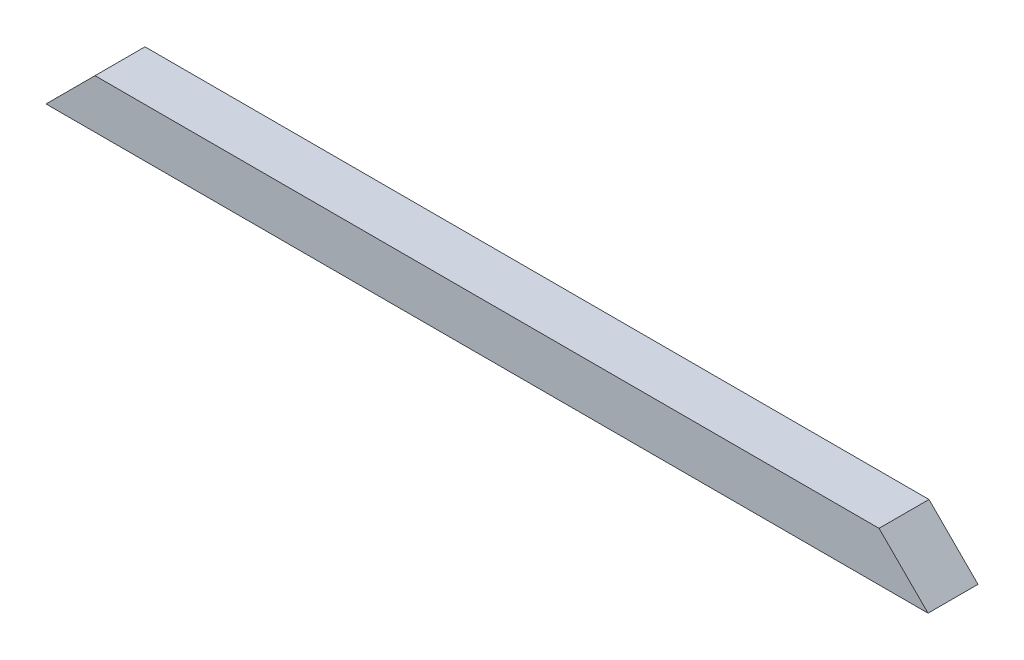
SolidWorks part; units mm, degrees
ref_plane "Alzado" through (0, 0, 0) normal (0, 0, 1) x (1, 0, 0)
ref_plane "Planta" through (0, 0, 0) normal (0, 1, 0) x (1, 0, 0)
ref_plane "Vista lateral" through (0, 0, 0) normal (1, 0, 0) x (0, 0, -1)
sketch "Croquis1" plane through (0, 0, 0) normal (0, 0, 1) x (1, 0, 0)
  line L1 (457.2, -25.4) -> (-457.2, -25.4)
  line L2 (457.2, -25.4) -> (457.2, 25.4)
  line L3 (457.2, 25.4) -> (-457.2, 25.4)
  line L4 (-457.2, -25.4) -> (-457.2, 25.4)
  line L5 (457.2, -25.4) -> (-457.2, 25.4) construction
  line L6 (457.2, 25.4) -> (-457.2, -25.4) construction
  point P0 (0, 0)
  dimension "D1" = 914.4
  dimension "D2" = 50.8
extrude "Saliente-Extruir1" add sketch "Croquis1" along normal blind 50.8 and the other way blind 1
sketch "Croquis3" plane through (0, 0, 50.8) normal (0, 0, 1) x (1, 0, 0)
  line L0 (-457.2, -25.4) -> (457.2, -25.4) construction
  line L1 (-457.2, 25.4) -> (-437.2, 25.4)
  line L2 (-457.2, 25.4) -> (-457.2, -25.4)
  line L3 (-457.2, -25.4) -> (-437.2, -25.4)
  line L4 (-437.2, 25.4) -> (-437.2, -25.4)
  line L5 (-437.2, 25.4) -> (-457.2, -25.4)
  line L6 (0, 0) -> (0, 51.0036) construction
  line M2 (-457.2, 25.4) -> (-457.2, -25.4)
  line M5 (457.2, 25.4) -> (-457.2, 25.4)
  dimension "D1" = 20
extrude "Cortar-Extruir2" cut sketch "Croquis3" against normal through all contours L5 M5 M2
sketch "Croquis4" plane through (0, 0, -1) normal (0, 0, -1) x (-1, 0, 0)
  line L0 (457.2, -25.4) -> (-457.2, -25.4) construction
  line L1 (-457.2, 25.4) -> (-437.2, 25.4)
  line L2 (-457.2, 25.4) -> (-457.2, -25.4)
  line L3 (-457.2, -25.4) -> (-437.2, -25.4)
  line L4 (-437.2, 25.4) -> (-437.2, -25.4)
  line L5 (-457.2, -25.4) -> (-437.2, 25.4)
  line M3 (437.2, 25.4) -> (-457.2, 25.4)
  line M4 (-457.2, 25.4) -> (-457.2, -25.4)
  dimension "D1" = 20
extrude "Cortar-Extruir3" cut sketch "Croquis4" against normal through all contours L5 M4 M3
sketch "Croquis6" plane through (0, 0, 50.8) normal (0, 0, 1) x (1, 0, 0)
  line L0 (437.2, 25.4) -> (-437.2, 25.4) construction
  line L1 (-457.2, -25.4) -> (-406.4, -25.4)
  line L2 (-457.2, -25.4) -> (-457.2, 25.4)
  line L3 (-457.2, 25.4) -> (-406.4, 25.4)
  line L4 (-406.4, -25.4) -> (-406.4, 25.4)
  line L5 (-406.4, 25.4) -> (-457.2, -25.4)
  line L6 (0, 0) -> (0, 184.0225) construction
  line L7 (457.2, -25.4) -> (457.2, 25.4)
  line L8 (406.4, 25.4) -> (457.2, -25.4)
  line L9 (457.2, 25.4) -> (406.4, 25.4)
  line M5 (457.2, -25.4) -> (437.2, 25.4)
  line M6 (437.2, 25.4) -> (-437.2, 25.4)
  line M7 (-437.2, 25.4) -> (-457.2, -25.4)
  dimension "D1" = 50.8
extrude "Cortar-Extruir4" cut sketch "Croquis6" against normal through all contours L5 M6 M7 | L8 M6 M5
